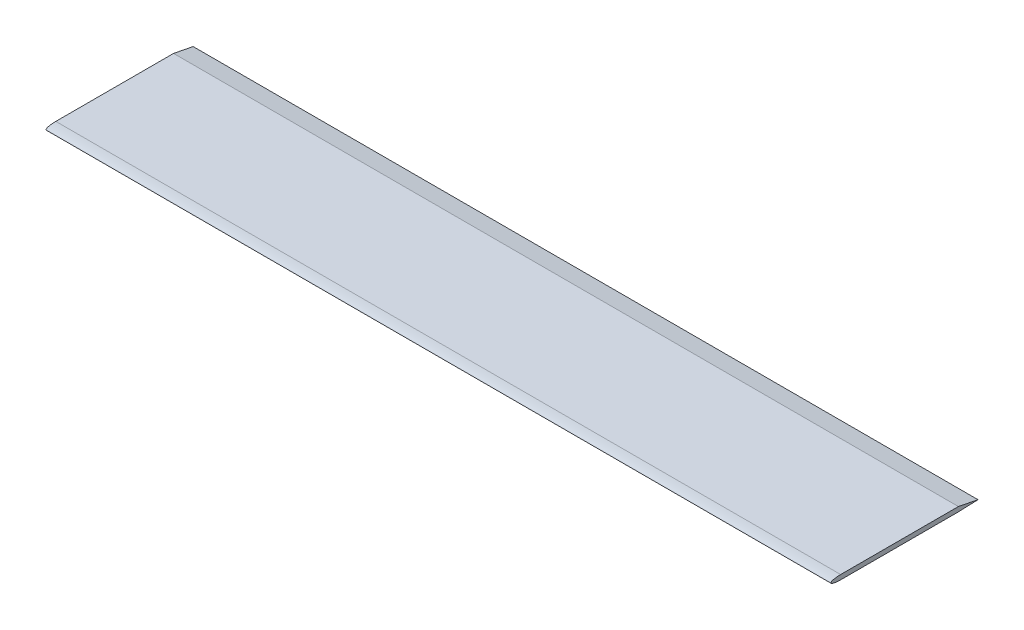
SolidWorks part; units mm, degrees
ref_plane "Front Plane" through (0, 0, 0) normal (0, 0, 1) x (1, 0, 0)
ref_plane "Top Plane" through (0, 0, 0) normal (0, 1, 0) x (1, 0, 0)
ref_plane "Right Plane" through (0, 0, 0) normal (1, 0, 0) x (0, 0, -1)
sketch "Sketch1" plane through (0, 0, 0) normal (1, 0, 0) x (0, 0, -1)
  line L3 (150.7285, 3) -> (176.1285, -2)
  line L4 (176.1285, -2) -> (150.7285, -3)
  line L5 (150.7285, 3) -> (-1.6715, 3)
  line L6 (150.7285, 3) -> (150.7285, -3)
  line L7 (150.7285, -3) -> (-1.6715, -3)
  line L8 (-1.6715, 3) -> (-1.6715, -3)
  ellipse E0 centre (-1.6715, 0) end of major axis (-14.3715, 0) minor radius 3
  dimension "D1" = 152.4
  dimension "D2" = 25.4
  dimension "D3" = 6
  dimension "D4" = 25.4
  dimension "D5" = 5
extrude "Boss-Extrude1" add sketch "Sketch1" along normal blind 1016 contours E0 L7 L6 L5 | L8 E0 | L8 E0 | L3 L6 L4
